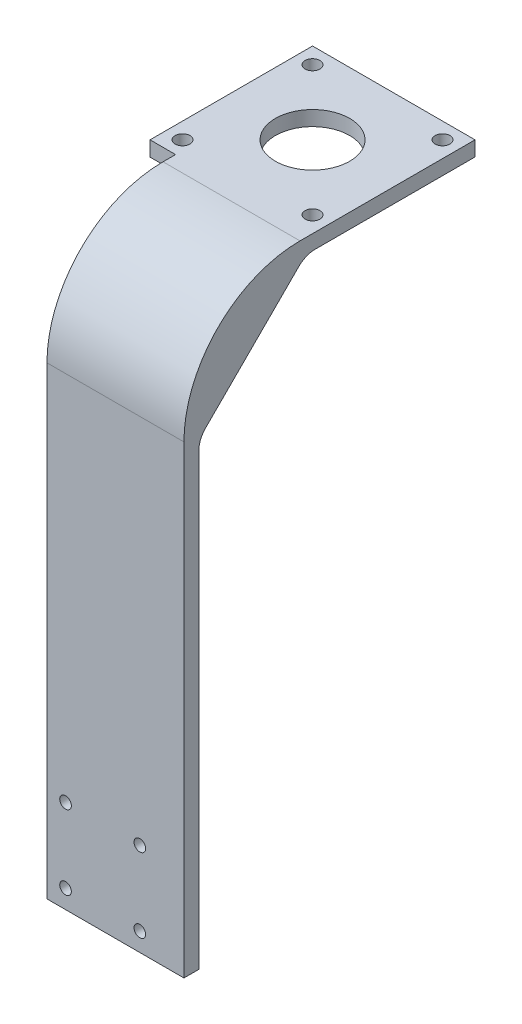
SolidWorks part; units mm, degrees
ref_plane "Front Plane" through (0, 0, 0) normal (0, 0, 1) x (1, 0, 0)
ref_plane "Top Plane" through (0, 0, 0) normal (0, 1, 0) x (1, 0, 0)
ref_plane "Right Plane" through (0, 0, 0) normal (1, 0, 0) x (0, 0, -1)
sketch "Sketch1" plane through (0, 0, 0) normal (0, 0, 1) x (1, 0, 0)
  line L1 (-12, -12) -> (12, -12)
  line L2 (-12, -12) -> (-12, 113)
  line L3 (-12, 113) -> (12, 113)
  line L4 (12, -12) -> (12, 113)
  line L5 (-8, 8) -> (8, 8) construction
  line L6 (-8, 8) -> (-8, -8) construction
  line L7 (-8, -8) -> (8, -8) construction
  line L8 (8, 8) -> (8, -8) construction
  circle A0 centre (-8, 8) radius 1.25
  circle A1 centre (8, 8) radius 1.25
  circle A2 centre (8, -8) radius 1.25
  circle A3 centre (-8, -8) radius 1.25
  point P4 (0, -12)
  point P10 (-8, 0)
  point P11 (0, 8)
  dimension "D2" = 2.5
  dimension "D1" = 16
  dimension "D3" = 24
  dimension "D4" = 4
  dimension "D5" = 125
extrude "Boss-Extrude1" add sketch "Sketch1" along normal blind 3.2
sketch "Sketch2" plane through (0, 0, 0) normal (0, 0, -1) x (-1, 0, 0)
  line L0 (12, 113) -> (12, -12) construction
  line L1 (-12, 113) -> (12, 113)
  line L2 (-12, 113) -> (-12, 109.8)
  line L3 (-12, 109.8) -> (12, 109.8)
  line L4 (12, 113) -> (12, 109.8)
  dimension "D1" = 3.2
extrude "Boss-Extrude2" add sketch "Sketch2" along normal blind 42
sketch "Sketch3" plane through (0, 113, 0) normal (0, 1, 0) x (1, 0, 0)
  line L0 (-12, 42) -> (12, 42) construction
  line L1 (-14, 28) -> (14, 28) construction
  line L2 (-14, 28) -> (-14, 56) construction
  line L3 (-14, 56) -> (14, 56) construction
  line L4 (14, 28) -> (14, 56) construction
  line L5 (-14, 28) -> (14, 56) construction
  line L6 (-14, 56) -> (14, 28) construction
  line L8 (17.5, 59.5) -> (-17.5, 59.5)
  line L9 (17.5, 59.5) -> (17.5, 24.5)
  line L10 (17.5, 24.5) -> (-17.5, 24.5)
  line L11 (-17.5, 59.5) -> (-17.5, 24.5)
  line L12 (17.5, 59.5) -> (-17.5, 24.5) construction
  line L13 (17.5, 24.5) -> (-17.5, 59.5) construction
  circle A0 centre (14, 28) radius 1.6
  circle A1 centre (14, 56) radius 1.6
  circle A2 centre (-14, 56) radius 1.6
  circle A3 centre (-14, 28) radius 1.6
  point P0 (0, 42)
  point P11 (0, 42)
  dimension "D1" = 3.2
  dimension "D2" = 28
  dimension "D3" = 35
extrude "Boss-Extrude3" add sketch "Sketch3" against normal up to surface (3.2 mm away) up to face at (0, 109.8, -21)
sketch "Sketch4" plane through (0, 109.8, 0) normal (0, -1, 0) x (1, 0, 0)
  line L0 (-17.5, -59.5) -> (17.5, -24.5) construction
  circle A0 centre (0, -42) radius 8
  dimension "D1" = 16
extrude "Cut-Extrude1" cut sketch "Sketch4" against normal up to surface (3.2 mm away) up to face at (0, 113, -26.325)
ref_plane "Plane1" through (12, 109.8, 0) normal (-1, 0, 0) x (0, 0, 1)
chamfer "Chamfer1" distance 23 angle 45 1 edges at (0, 109.8, 0)
fillet "Fillet1" radius 25 1 edges at (0, 113, 3.2)
fillet "Fillet2" radius 5 2 edges at (0, 109.8, -23) (0, 86.8, 0)
sketch "Sketch7" plane through (12, 0, 0) normal (1, 0, 0) x (0, 0, -1)
  line L12 (24.5, 113) -> (21.8, 113)
  line L13 (-3.2, 88) -> (-3.2, -12)
  line L14 (-3.2, -12) -> (0, -12)
  line L15 (0, -12) -> (0, 84.7289)
  line L16 (1.4645, 88.2645) -> (21.5355, 108.3355)
  line L17 (24.5, 109.7673) -> (24.5, 113)
  line L18 (24.5, 113) -> (21.8, 113)
  line L19 (-3.2, 88) -> (-3.2, -12)
  line L20 (-3.2, -12) -> (0, -12)
  line L21 (0, -12) -> (0, 84.7289)
  line L22 (1.4645, 88.2645) -> (21.5355, 108.3355)
  line L23 (24.5, 109.7673) -> (24.5, 113)
  arc A6 (21.8, 113) -> (-3.2, 88) centre (21.8, 88) ccw
  arc A7 (1.4645, 88.2645) -> (0, 84.7289) centre (5, 84.7289) ccw
  arc A8 (24.5, 109.7673) -> (21.5355, 108.3355) centre (25.0711, 104.8) ccw
  arc A9 (21.8, 113) -> (-3.2, 88) centre (21.8, 88) ccw
  arc A10 (1.4645, 88.2645) -> (0, 84.7289) centre (5, 84.7289) ccw
  arc A11 (24.5, 109.7673) -> (21.5355, 108.3355) centre (25.0711, 104.8) ccw
  dimension "D1" = 0
extrude "Boss-Extrude4" add sketch "Sketch7" along normal up to surface (5.5 mm away) up to face at (17.5, 111.0751, -38.6141)
